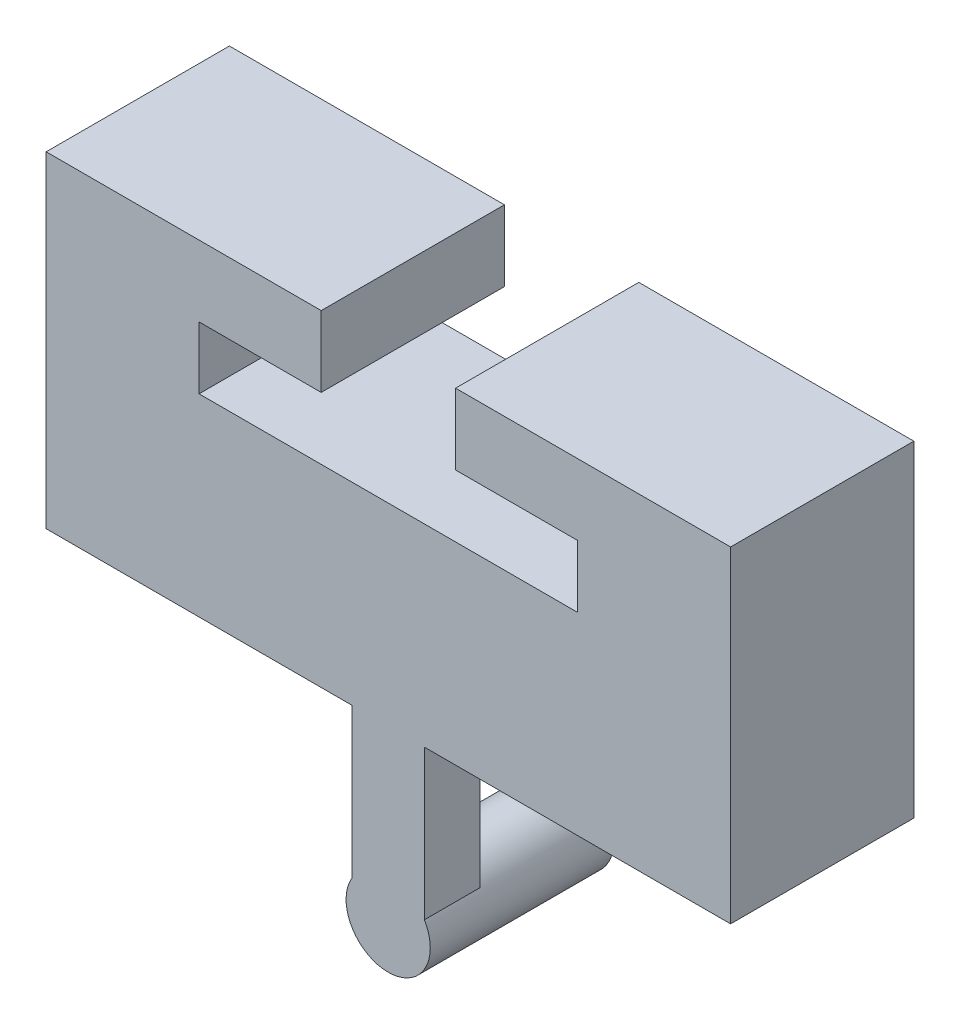
SolidWorks part; units mm, degrees
ref_plane "Front Plane" through (0, 0, 0) normal (0, 0, 1) x (1, 0, 0)
ref_plane "Top Plane" through (0, 0, 0) normal (0, 1, 0) x (1, 0, 0)
ref_plane "Right Plane" through (0, 0, 0) normal (1, 0, 0) x (0, 0, -1)
sketch "Sketch1" plane through (0, 0, 0) normal (0, 0, 1) x (1, 0, 0)
  line L0 (0, 0) -> (142.3195, 0)
  line L1 (142.3195, 0) -> (142.3195, 67.883)
  line L2 (142.3195, 67.883) -> (85.1297, 67.883)
  line L3 (85.1297, 67.883) -> (85.1297, 53.1441)
  line L4 (85.1297, 53.1441) -> (110.5297, 53.1441)
  line L5 (110.5297, 53.1441) -> (110.5297, 40.1901)
  line L6 (110.5297, 40.1901) -> (31.7897, 40.1901)
  line L7 (31.7897, 40.1901) -> (31.7897, 53.1441)
  line L8 (31.7897, 53.1441) -> (57.1897, 53.1441)
  line L9 (57.1897, 53.1441) -> (57.1897, 67.883)
  line L10 (57.1897, 67.883) -> (0, 67.883)
  line L11 (0, 67.883) -> (0, 0)
  point P3 (0, 0)
  point P14 (0, 0)
  dimension "D1" = 78.74
  dimension "D2" = 14.7389
  dimension "D3" = 14.7389
  dimension "D4" = 31.7897
  dimension "D5" = 40.1901
  dimension "D6" = 31.7897
  dimension "D7" = 25.4
  dimension "D8" = 25.4
  dimension "D9" = 12.954
  dimension "D10" = 12.954
extrude "Boss-Extrude1" add sketch "Sketch1" along normal blind 38.1
sketch "Sketch2" plane through (0, 0, 38.1) normal (0, 0, 1) x (1, 0, 0)
  line L0 (71.1597, 40.1901) -> (71.1597, 0) construction
  line L1 (110.5297, 40.1901) -> (31.7897, 40.1901) construction
  line L2 (0, 0) -> (142.3195, 0) construction
  circle A0 centre (71.12, -35.56) radius 8.7503
  dimension "D1" = 17.5006
  dimension "D2" = 35.56
extrude "Boss-Extrude2" add sketch "Sketch2" against normal blind 38.1
sketch "Sketch8" plane through (0, 0, 38.1) normal (0, 0, 1) x (1, 0, 0)
  line L0 (63.592, -40.0206) -> (63.592, 0)
  line L1 (0, 0) -> (142.3195, 0) construction
  line L2 (78.648, -40.0206) -> (78.648, 0)
  line L3 (78.648, 0) -> (63.592, 0)
  circle A0 centre (71.12, -35.56) radius 8.7503 construction
  circle A2 centre (71.12, -35.56) radius 8.7503
  arc A3 (63.592, -40.0206) -> (78.648, -40.0206) centre (71.12, -35.56) ccw
  dimension "D1" = 0
extrude "Boss-Extrude6" add sketch "Sketch8" against normal blind 11.5723
equation "\"E\"= 470000"
equation "\"SF\"= 4"
equation "\"F\"= 250"
equation "\"Deflection\"= .005"
equation "\"IA\"= ( 5 * 500 * \"SF\" * 1 ) / ( 384 * \"E\" * \"Deflection\" )"
equation "\"Feature A Diameter \"= ( ( 64 * \"IA\" ) / pi ) ^ ( 1 / 4 )"
equation "\"Feature B Width\"= ( \"F\" * \"SF\" ) / ( \"E\" * \"Deflection\" * .934 )"
equation "\"IC\" = ( 5 * 500 * \"SF\" * ( 92.35 ) ) / ( 384 * \"E\" * \"Deflection\" )"
equation "\"Feature C height\"= ( ( 12 * \"IC\" ) / 3.1 ) ^ ( 1 / 3 )"
equation "\"Feature D width\" = ( \"F\" * \"SF\" * 1.5 ) / ( \"E\" * \"Deflection\" * .51 )"
equation "\"Feature E\"= ( \"F\" * \"SF\" * 1.5 ) / ( \"E\" * \"Deflection\" * 1.1 )"
equation "\"D3@Sketch1\"=\"Feature E\""
equation "\"D2@Sketch1\"=\"Feature E\""
equation "\"D4@Sketch1\"=\"Feature D width\""
equation "\"D6@Sketch1\"=\"Feature D width\" "
equation "\"D5@Sketch1\"=\"Feature C height\""
equation "\"D1@Boss-Extrude6\"=\"Feature B Width\""
